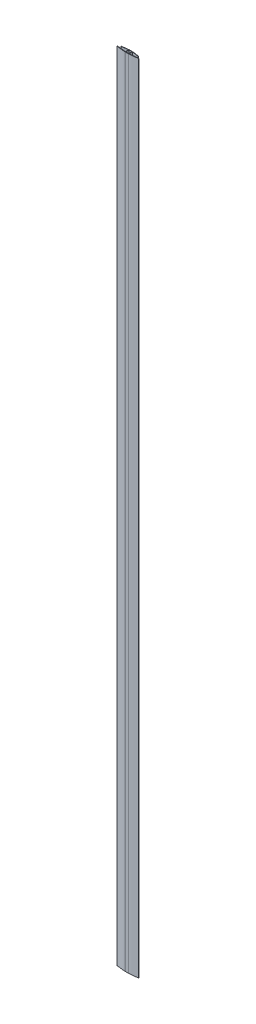
SolidWorks part; units mm, degrees
ref_plane "Front Plane" through (0, 0, 0) normal (0, 0, 1) x (1, 0, 0)
ref_plane "Top Plane" through (0, 0, 0) normal (0, 1, 0) x (1, 0, 0)
ref_plane "Right Plane" through (0, 0, 0) normal (1, 0, 0) x (0, 0, -1)
sketch "Sketch1" plane through (0, 0, 0) normal (0, 1, 0) x (1, 0, 0)
  line L0 (0, -5.4) -> (0, 5.4) construction
  line L1 (-36, -5.4) -> (36, -5.4) construction
  line L2 (-36, -5.4) -> (-36, 5.4) construction
  line L3 (-36, 5.4) -> (36, 5.4) construction
  line L4 (36, -5.4) -> (36, 5.4) construction
  line L5 (-36, -5.4) -> (36, 5.4) construction
  line L6 (-36, 5.4) -> (36, -5.4) construction
  line L7 (-6.2, -5.4) -> (-6.2, 5.4)
  line L8 (-5, -5.4) -> (-5, 5.4)
  line L9 (-5, 5.4) -> (0, 5.4)
  line L10 (-5, 6.6) -> (0, 6.6)
  line L11 (-5, -5.4) -> (0, -5.4)
  line L12 (-5, -6.6) -> (0, -6.6)
  line L13 (-36, -2.25) -> (-36, 2.25) construction
  line L14 (-36, 0) -> (0, 0) construction
  line L15 (-36, 2.25) -> (0, 2.25) construction
  line L16 (36, -2.25) -> (36, -3.4767)
  line L17 (-29.5, 2.25) -> (-29.5, -5.4) construction
  line L18 (-14.8127, 5.4) -> (2.4128, 5.4) construction
  line L19 (-29.5, 2.25) -> (-29.5, 3.45) construction
  line L20 (-29.5, 3.2115) -> (-29.5, 2.4138)
  line L21 (-5, -6.6) -> (-5.715, -6.6296)
  line L23 (-36, -2.25) -> (-36, -3.4767)
  line L24 (5, -5.4) -> (5, 5.4)
  line L25 (6.2, -5.4) -> (6.2, 5.4)
  line L28 (5, -6.6) -> (5.715, -6.6296)
  line L29 (5, -6.6) -> (0, -6.6)
  line L30 (5, -5.4) -> (0, -5.4)
  line L31 (29.5, 2.25) -> (29.5, 3.45) construction
  line L32 (29.5, 3.2115) -> (29.5, 2.4138)
  line L33 (5, 6.6) -> (0, 6.6)
  line L34 (5, 5.4) -> (0, 5.4)
  arc A0 (-29.3222, 2.215) -> (-29.5, 2.4138) centre (-29.3, 2.4138) cw
  arc A1 (-29.5, 3.2115) -> (-29.2821, 3.4107) centre (-29.3, 3.2115) cw
  arc A2 (29.5, 3.2115) -> (29.2821, 3.4107) centre (29.3, 3.2115) ccw
  arc A3 (29.3222, 2.215) -> (29.5, 2.4138) centre (29.3, 2.4138) ccw
  spline S0 degree 2 poles (-36, -2.25) (-9.4015, -5.3792) (-6.2, -5.4) knots 0 0 0 1 1 1
  spline S1 degree 3 poles (-6.2, 5.4) (-9.6792, 5.4) (-20.112, 3.6814) (-28.1938, 2.089) (-29.3222, 2.215) knots 0 0 0 0 0.484753 0.969505 0.969505 0.969505 0.969505
  spline S2 degree 3 poles (-5, 6.6) (-9.2072, 6.5659) (-20.1691, 4.8652) (-28.1029, 3.3046) (-29.2821, 3.4107) knots 0 0 0 0 0.481876 0.963751 0.963751 0.963751 0.963751
  spline S3 degree 2 poles (-36, -3.4767) (-11.556, -6.85) (-5.715, -6.6296) knots 0 0 0 1 1 1
  spline S4 degree 2 poles (36, -3.4767) (11.556, -6.85) (5.715, -6.6296) knots 0 0 0 1 1 1
  spline S5 degree 2 poles (36, -2.25) (9.4015, -5.3792) (6.2, -5.4) knots 0 0 0 1 1 1
  spline S7 degree 3 poles (5, 6.6) (9.2072, 6.5659) (20.1691, 4.8652) (28.1029, 3.3046) (29.2821, 3.4107) knots 0 0 0 0 0.481876 0.963751 0.963751 0.963751 0.963751
  spline S8 degree 3 poles (6.2, 5.4) (9.6792, 5.4) (20.112, 3.6814) (28.1938, 2.089) (29.3222, 2.215) knots 0 0 0 0 0.484753 0.969505 0.969505 0.969505 0.969505
  point P0 (0, 0)
  dimension "D10" = 0.2
  dimension "D1" = 72
  dimension "D2" = 10.8
  dimension "D7" = 2.25
  dimension "D9" = 29.5
  dimension "D3" = 1.2
  dimension "D4" = 5
  dimension "D5" = 1.2
  dimension "D6" = 1.2
extrude "Boss-Extrude1" add sketch "Sketch1" along normal blind 2693.01
equation "\"D9@Sketch1\"=59/2"
